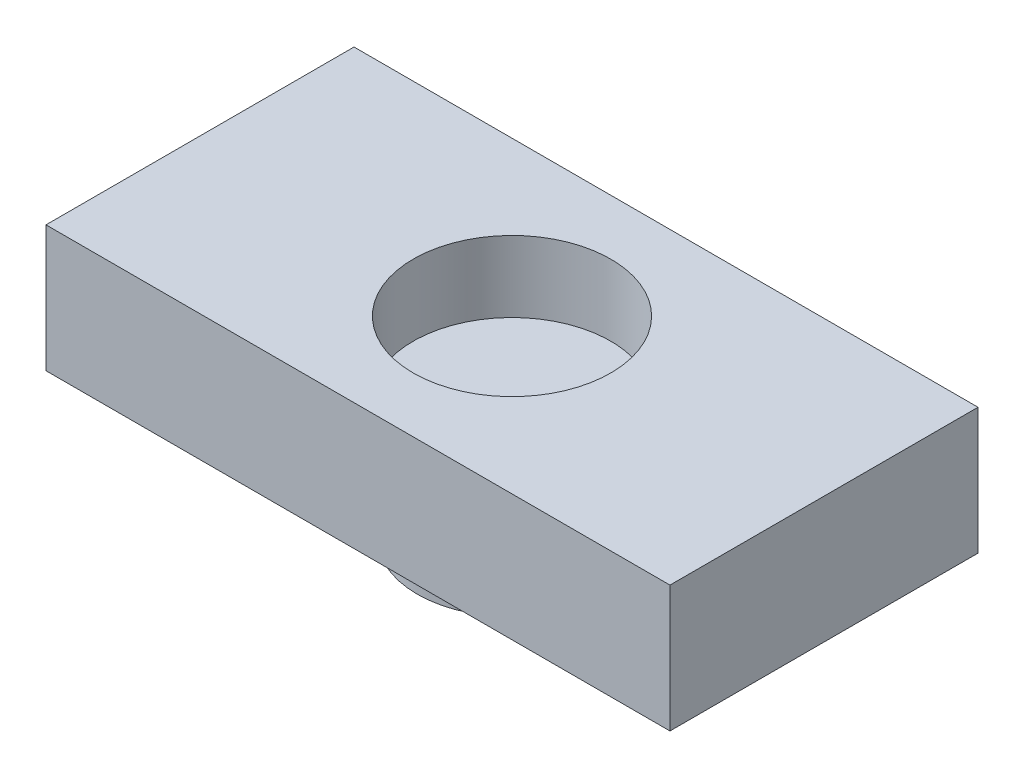
SolidWorks part; units mm, degrees
ref_plane "Спереди" through (0, 0, 0) normal (0, 0, 1) x (1, 0, 0)
ref_plane "Сверху" through (0, 0, 0) normal (0, 1, 0) x (1, 0, 0)
ref_plane "Справа" through (0, 0, 0) normal (1, 0, 0) x (0, 0, -1)
sketch "Эскиз1" plane through (0, 0, 0) normal (0, 1, 0) x (1, 0, 0)
  line L1 (7.9, -3.9) -> (-7.9, -3.9)
  line L2 (7.9, -3.9) -> (7.9, 3.9)
  line L3 (7.9, 3.9) -> (-7.9, 3.9)
  line L4 (-7.9, -3.9) -> (-7.9, 3.9)
  line L5 (7.9, -3.9) -> (-7.9, 3.9) construction
  line L6 (7.9, 3.9) -> (-7.9, -3.9) construction
  circle A0 centre (0, 0) radius 2.4
  point P0 (0, 0)
  dimension "D3" = 4.8
  dimension "D1" = 15.8
  dimension "D2" = 7.8
extrude "Бобышка-Вытянуть1" add sketch "Эскиз1" along normal blind 3.2 contours A0 | L4 L1 L2 L3 A0
sketch "Эскиз2" plane through (0, 0, 0) normal (0, 1, 0) x (1, 0, 0)
  circle A0 centre (0, 0) radius 2.4
  circle A1 centre (0, 0) radius 1.6
  dimension "D1" = 4.8
  dimension "D2" = 3.2
extrude "Бобышка-Вытянуть2" add sketch "Эскиз2" against normal blind 1.7
sketch "Эскиз3" plane through (0, 3.2, 0) normal (0, 1, 0) x (1, 0, 0)
  circle A0 centre (0, 0) radius 2.5
extrude "Вырез-Вытянуть1" cut sketch "Эскиз3" against normal blind 1.8
